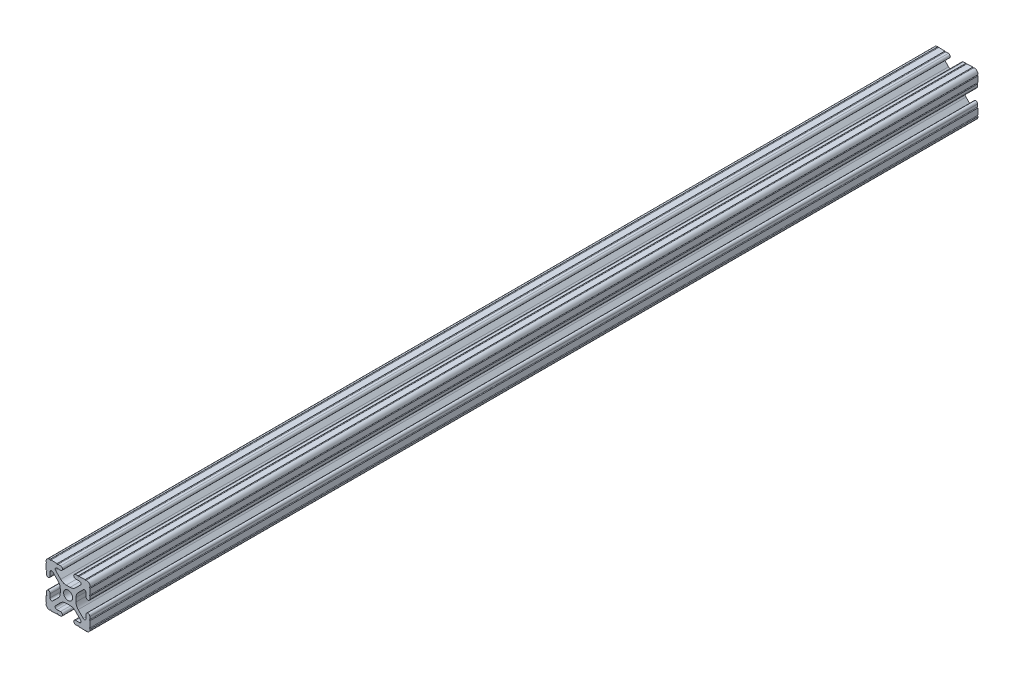
SolidWorks part; units mm, degrees
ref_plane "Front Plane" through (0, 0, 0) normal (0, 0, 1) x (1, 0, 0)
ref_plane "Top Plane" through (0, 0, 0) normal (0, 1, 0) x (1, 0, 0)
ref_plane "Right Plane" through (0, 0, 0) normal (1, 0, 0) x (0, 0, -1)
sketch "Sketch1" plane through (0, 0, 0) normal (0, 0, 1) x (1, 0, 0)
  line L0 (0, 12.7) -> (-12.7814, 12.7) construction
  line L1 (-4.5085, 0) -> (-4.5085, 2.9459)
  line L2 (-6.0437, 12.5461) -> (-10.0976, 12.6876) construction
  line L3 (-11.5616, 12.4229) -> (-4.3159, 12.1699) construction
  line L4 (-6.4364, 10.3486) -> (-6.3592, 12.5571) construction
  line L6 (-2.9459, 4.5085) -> (0, 4.5085)
  line L7 (0, 0) -> (0, 12.7) construction
  line L8 (0, 0) -> (-12.7814, 0) construction
  line L9 (0.7813, 0.7813) -> (-0.7813, -0.7813) construction
  line L10 (-2.9459, 4.5085) -> (-7.1484, 8.711)
  line L11 (-4.5085, 2.9459) -> (-8.711, 7.1484)
  line L13 (0, 0) -> (-12.7814, 12.7814) construction
  line L14 (-10.4131, 12.6987) -> (-4.3048, 12.4853)
  line L15 (-4.3048, 12.4853) -> (-4.382, 10.2769) construction
  line L16 (-4.382, 10.2769) -> (-6.4364, 10.3486)
  line L17 (-12.6987, 10.4131) -> (-12.4853, 4.3048)
  line L18 (-10.2769, 4.382) -> (-10.3486, 6.4364)
  circle A0 centre (0, 0) radius 2.6035
  arc A1 (-4.382, 10.2769) -> (-4.3048, 12.4853) centre (-4.3434, 11.3811) ccw
  arc A2 (-7.1484, 8.711) -> (-6.4364, 10.3486) centre (-6.4698, 9.3896) cw
  arc A3 (-8.711, 7.1484) -> (-10.3486, 6.4364) centre (-9.3896, 6.4698) ccw
  arc A4 (-10.2769, 4.382) -> (-12.4853, 4.3048) centre (-11.3811, 4.3434) cw
  arc A5 (-10.4131, 12.6987) -> (-12.6987, 10.4131) centre (-10.4902, 10.4902) ccw
  arc A6 (-10.4131, 12.6987) -> (-9.7821, 12.6766) centre (-10.0976, 12.6876) ccw
  arc A7 (-6.3592, 12.5571) -> (-5.7282, 12.5351) centre (-6.0437, 12.5461) ccw
  arc A8 (-12.5571, 6.3592) -> (-12.5351, 5.7282) centre (-12.5461, 6.0437) cw
  arc A9 (-12.6987, 10.4131) -> (-12.6766, 9.7821) centre (-12.6876, 10.0976) cw
  dimension "D1" = 5.207
  dimension "D5" = 14.859
  dimension "D9" = 2
  dimension "D2" = 25.4
  dimension "D12" = 0.6314
  dimension "D10" = 2.2098
  dimension "D3" = 9.017
  dimension "D4" = 9.017
  dimension "D6" = 25.4
  dimension "D7" = 6.477
  dimension "D8" = 2.2098
  dimension "D11" = 12.7
sketch "Sketch3" plane through (0, 0, 0) normal (0, 0, 1) x (1, 0, 0)
  line L0 (-2.9459, 4.5085) -> (0, 4.5085) construction
  line L1 (-2.9459, 4.5085) -> (-7.1484, 8.711) construction
  line L2 (-4.382, 10.2769) -> (-6.4364, 10.3486) construction
  line L3 (-10.4131, 12.6987) -> (-4.3048, 12.4853) construction
  line L4 (-4.5085, 0) -> (-4.5085, 2.9459) construction
  line L5 (-4.5085, 2.9459) -> (-8.711, 7.1484) construction
  line L6 (-10.2769, 4.382) -> (-10.3486, 6.4364) construction
  line L7 (-12.6987, 10.4131) -> (-12.4853, 4.3048) construction
  line L8 (-1.1153, 4.5085) -> (1.1153, 4.5085)
  line L9 (-4.2404, 5.803) -> (-7.1484, 8.711)
  line L10 (-4.382, 10.2769) -> (-6.4364, 10.3486)
  line L11 (-9.7821, 12.6766) -> (-6.3592, 12.5571)
  line L12 (-4.5085, -1.1153) -> (-4.5085, 1.1153)
  line L13 (-5.803, 4.2404) -> (-8.711, 7.1484)
  line L14 (-10.2769, 4.382) -> (-10.3486, 6.4364)
  line L15 (-12.6766, 9.7821) -> (-12.5571, 6.3592)
  line L16 (-5.7282, 12.5351) -> (-4.3048, 12.4853)
  line L17 (-12.5351, 5.7282) -> (-12.4853, 4.3048)
  line L18 (0, 0) -> (0, 12.7) construction
  line L19 (0, 0) -> (-12.7814, 0) construction
  line L20 (12.5351, 5.7282) -> (12.4853, 4.3048)
  line L21 (5.7282, 12.5351) -> (4.3048, 12.4853)
  line L22 (12.6766, 9.7821) -> (12.5571, 6.3592)
  line L23 (10.2769, 4.382) -> (10.3486, 6.4364)
  line L24 (5.803, 4.2404) -> (8.711, 7.1484)
  line L25 (4.5085, -1.1153) -> (4.5085, 1.1153)
  line L26 (9.7821, 12.6766) -> (6.3592, 12.5571)
  line L27 (4.382, 10.2769) -> (6.4364, 10.3486)
  line L28 (4.2404, 5.803) -> (7.1484, 8.711)
  line L29 (4.2404, -5.803) -> (7.1484, -8.711)
  line L30 (4.382, -10.2769) -> (6.4364, -10.3486)
  line L31 (9.7821, -12.6766) -> (6.3592, -12.5571)
  line L32 (5.803, -4.2404) -> (8.711, -7.1484)
  line L33 (10.2769, -4.382) -> (10.3486, -6.4364)
  line L34 (12.6766, -9.7821) -> (12.5571, -6.3592)
  line L35 (5.7282, -12.5351) -> (4.3048, -12.4853)
  line L36 (12.5351, -5.7282) -> (12.4853, -4.3048)
  line L37 (-12.5351, -5.7282) -> (-12.4853, -4.3048)
  line L38 (-5.7282, -12.5351) -> (-4.3048, -12.4853)
  line L39 (-12.6766, -9.7821) -> (-12.5571, -6.3592)
  line L40 (-10.2769, -4.382) -> (-10.3486, -6.4364)
  line L41 (-5.803, -4.2404) -> (-8.711, -7.1484)
  line L42 (-9.7821, -12.6766) -> (-6.3592, -12.5571)
  line L43 (-4.382, -10.2769) -> (-6.4364, -10.3486)
  line L44 (-4.2404, -5.803) -> (-7.1484, -8.711)
  line L45 (-1.1153, -4.5085) -> (1.1153, -4.5085)
  arc A0 (-10.4131, 12.6987) -> (-9.7821, 12.6766) centre (-10.0976, 12.6876) ccw construction
  arc A1 (-6.4364, 10.3486) -> (-7.1484, 8.711) centre (-6.4698, 9.3896) ccw construction
  arc A2 (-4.382, 10.2769) -> (-4.3048, 12.4853) centre (-4.3434, 11.3811) ccw construction
  arc A3 (-8.711, 7.1484) -> (-10.3486, 6.4364) centre (-9.3896, 6.4698) ccw construction
  arc A4 (-12.4853, 4.3048) -> (-10.2769, 4.382) centre (-11.3811, 4.3434) ccw construction
  arc A5 (-6.3592, 12.5571) -> (-5.7282, 12.5351) centre (-6.0437, 12.5461) ccw construction
  arc A6 (-10.4131, 12.6987) -> (-12.6987, 10.4131) centre (-10.4902, 10.4902) ccw construction
  arc A7 (-12.6766, 9.7821) -> (-12.6987, 10.4131) centre (-12.6876, 10.0976) ccw construction
  arc A8 (-12.5351, 5.7282) -> (-12.5571, 6.3592) centre (-12.5461, 6.0437) ccw construction
  arc A9 (-10.4131, 12.6987) -> (-9.7821, 12.6766) centre (-10.0976, 12.6876) ccw
  arc A10 (-6.4364, 10.3486) -> (-7.1484, 8.711) centre (-6.4698, 9.3896) ccw
  arc A11 (-4.382, 10.2769) -> (-4.3048, 12.4853) centre (-4.3434, 11.3811) ccw
  arc A12 (-8.711, 7.1484) -> (-10.3486, 6.4364) centre (-9.3896, 6.4698) ccw
  arc A13 (-12.4853, 4.3048) -> (-10.2769, 4.382) centre (-11.3811, 4.3434) ccw
  arc A14 (-6.3592, 12.5571) -> (-5.7282, 12.5351) centre (-6.0437, 12.5461) ccw
  arc A15 (-10.4131, 12.6987) -> (-12.6987, 10.4131) centre (-10.4902, 10.4902) ccw
  arc A16 (-12.6766, 9.7821) -> (-12.6987, 10.4131) centre (-12.6876, 10.0976) ccw
  arc A17 (-12.5351, 5.7282) -> (-12.5571, 6.3592) centre (-12.5461, 6.0437) ccw
  arc A18 (-1.1153, 4.5085) -> (-4.2404, 5.803) centre (-1.1153, 8.9281) cw
  arc A19 (4.5085, 1.1153) -> (5.803, 4.2404) centre (8.9281, 1.1153) cw
  arc A20 (1.1153, 4.5085) -> (4.2404, 5.803) centre (1.1153, 8.9281) ccw
  arc A21 (-4.5085, 1.1153) -> (-5.803, 4.2404) centre (-8.9281, 1.1153) ccw
  arc A22 (12.5351, 5.7282) -> (12.5571, 6.3592) centre (12.5461, 6.0437) cw
  arc A23 (12.6766, 9.7821) -> (12.6987, 10.4131) centre (12.6876, 10.0976) cw
  arc A24 (10.4131, 12.6987) -> (12.6987, 10.4131) centre (10.4902, 10.4902) cw
  arc A25 (6.3592, 12.5571) -> (5.7282, 12.5351) centre (6.0437, 12.5461) cw
  arc A26 (12.4853, 4.3048) -> (10.2769, 4.382) centre (11.3811, 4.3434) cw
  arc A27 (8.711, 7.1484) -> (10.3486, 6.4364) centre (9.3896, 6.4698) cw
  arc A28 (4.382, 10.2769) -> (4.3048, 12.4853) centre (4.3434, 11.3811) cw
  arc A29 (6.4364, 10.3486) -> (7.1484, 8.711) centre (6.4698, 9.3896) cw
  arc A30 (10.4131, 12.6987) -> (9.7821, 12.6766) centre (10.0976, 12.6876) cw
  arc A31 (10.4131, -12.6987) -> (9.7821, -12.6766) centre (10.0976, -12.6876) ccw
  arc A32 (6.4364, -10.3486) -> (7.1484, -8.711) centre (6.4698, -9.3896) ccw
  arc A33 (4.382, -10.2769) -> (4.3048, -12.4853) centre (4.3434, -11.3811) ccw
  arc A34 (8.711, -7.1484) -> (10.3486, -6.4364) centre (9.3896, -6.4698) ccw
  arc A35 (12.4853, -4.3048) -> (10.2769, -4.382) centre (11.3811, -4.3434) ccw
  arc A36 (6.3592, -12.5571) -> (5.7282, -12.5351) centre (6.0437, -12.5461) ccw
  arc A37 (10.4131, -12.6987) -> (12.6987, -10.4131) centre (10.4902, -10.4902) ccw
  arc A38 (12.6766, -9.7821) -> (12.6987, -10.4131) centre (12.6876, -10.0976) ccw
  arc A39 (12.5351, -5.7282) -> (12.5571, -6.3592) centre (12.5461, -6.0437) ccw
  arc A40 (-4.5085, -1.1153) -> (-5.803, -4.2404) centre (-8.9281, -1.1153) cw
  arc A41 (1.1153, -4.5085) -> (4.2404, -5.803) centre (1.1153, -8.9281) cw
  arc A42 (4.5085, -1.1153) -> (5.803, -4.2404) centre (8.9281, -1.1153) ccw
  arc A43 (-1.1153, -4.5085) -> (-4.2404, -5.803) centre (-1.1153, -8.9281) ccw
  arc A44 (-12.5351, -5.7282) -> (-12.5571, -6.3592) centre (-12.5461, -6.0437) cw
  arc A45 (-12.6766, -9.7821) -> (-12.6987, -10.4131) centre (-12.6876, -10.0976) cw
  arc A46 (-10.4131, -12.6987) -> (-12.6987, -10.4131) centre (-10.4902, -10.4902) cw
  arc A47 (-6.3592, -12.5571) -> (-5.7282, -12.5351) centre (-6.0437, -12.5461) cw
  arc A48 (-12.4853, -4.3048) -> (-10.2769, -4.382) centre (-11.3811, -4.3434) cw
  arc A49 (-8.711, -7.1484) -> (-10.3486, -6.4364) centre (-9.3896, -6.4698) cw
  arc A50 (-4.382, -10.2769) -> (-4.3048, -12.4853) centre (-4.3434, -11.3811) cw
  arc A51 (-6.4364, -10.3486) -> (-7.1484, -8.711) centre (-6.4698, -9.3896) cw
  arc A52 (-10.4131, -12.6987) -> (-9.7821, -12.6766) centre (-10.0976, -12.6876) cw
  circle A53 centre (0, 0) radius 2.6035 construction
  circle A54 centre (0, 0) radius 2.6035
  point P135 (4.5085, 0)
  dimension "D2" = 4.4196
extrude "Extrude1" add sketch "Sketch3" along normal mid plane 510.05
equation "\"D10@Sketch1\" = \"D8@Sketch1\""
equation "\"D11@Sketch1\" = \"D6@Sketch1\"/2"
equation "\"D12@Sketch1\" = \"D8@Sketch1\"/3.5"
equation "\"D2@Sketch3\" = \"D8@Sketch1\"*2"
